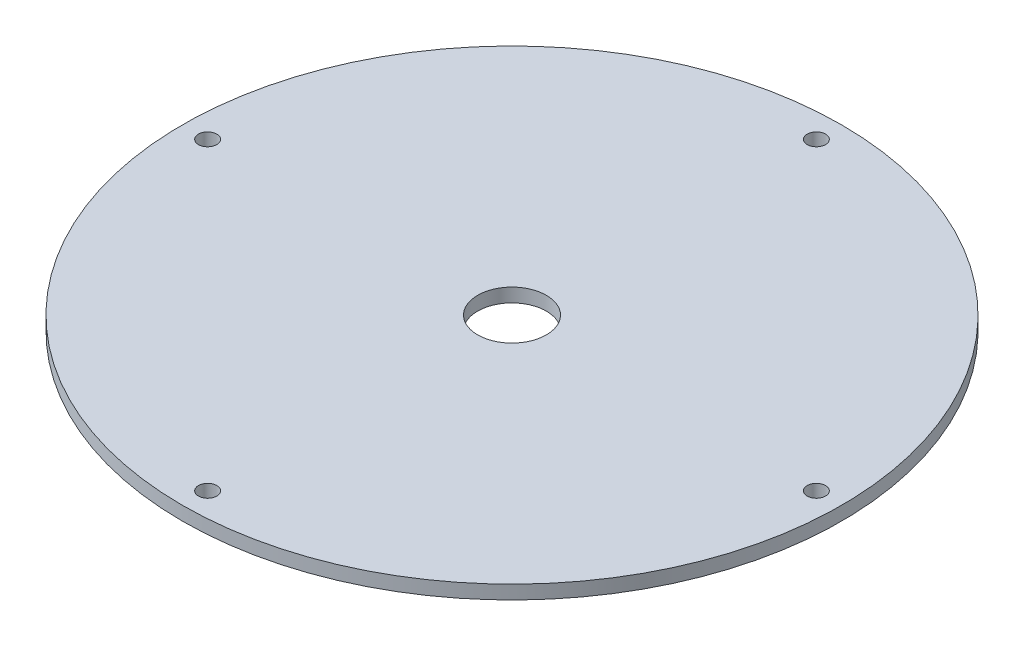
SolidWorks part; units mm, degrees
ref_plane "Front Plane" through (0, 0, 0) normal (0, 0, 1) x (1, 0, 0)
ref_plane "Top Plane" through (0, 0, 0) normal (0, 1, 0) x (1, 0, 0)
ref_plane "Right Plane" through (0, 0, 0) normal (1, 0, 0) x (0, 0, -1)
sketch "Sketch2" plane through (0, 0, 0) normal (0, 1, 0) x (1, 0, 0)
  line L0 (0, 80.5682) -> (0, -100.1481) construction
  line L1 (0, 0) -> (0, 66.5) construction
  circle A0 centre (0, 0) radius 72
  circle A1 centre (0, 0) radius 7.5
  circle A2 centre (0, 66.5) radius 2
  circle A3 centre (66.5, 0) radius 2
  circle A4 centre (0, -66.5) radius 2
  circle A5 centre (-66.5, 0) radius 2
  dimension "OuterDiameter" = 144
  dimension "InternalDiameter" = 15
  dimension "MountingBoltDiameter" = 4
  dimension "D2" = 66.5
  dimension "D3" = 0
  dimension "D1" = 4
extrude "Boss-Extrude1" add sketch "Sketch2" along normal blind 3
equation "\"ExternalDiameter\" = 144mm"
equation "\"ConnectorExternalDiameter\" = 144mm"
equation "\"ConnectorInternalDiameter\"= 122"
equation "\"InternalDiameter\"= 15"
equation "\"OuterDiameter@Sketch2\"= \"ExternalDiameter\""
equation "\"InternalDiameter@Sketch2\"= \"InternalDiameter\""
equation "\"MountingBoltDiameter\"= 4"
equation "\"MountingBoltDiameter@Sketch2\"= \"MountingBoltDiameter\""
equation "\"D2@Sketch2\" = 0.25 * ( \"ConnectorExternalDiameter\" + \"ConnectorInternalDiameter\" )"
